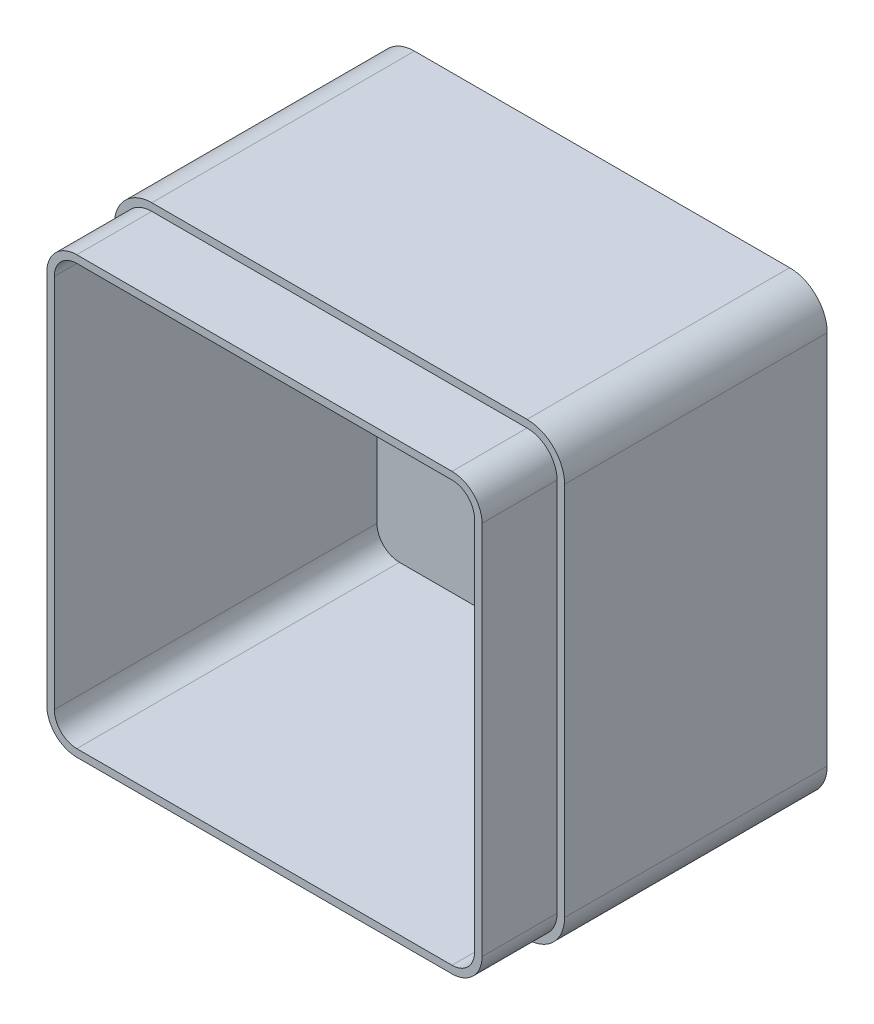
SolidWorks part; units mm, degrees
ref_plane "Front Plane" through (0, 0, 0) normal (0, 0, 1) x (1, 0, 0)
ref_plane "Top Plane" through (0, 0, 0) normal (0, 1, 0) x (1, 0, 0)
ref_plane "Right Plane" through (0, 0, 0) normal (1, 0, 0) x (0, 0, -1)
sketch "Sketch2" plane through (0, 0, 0) normal (0, 0, 1) x (1, 0, 0)
  line L1 (-46.1775, 31.2287) -> (73.8225, 31.2287)
  line L2 (-46.1775, 31.2287) -> (-46.1775, -88.7713)
  line L3 (-46.1775, -88.7713) -> (73.8225, -88.7713)
  line L4 (73.8225, 31.2287) -> (73.8225, -88.7713)
  dimension "D1" = 120
  dimension "D2" = 120
extrude "Boss-Extrude1" add sketch "Sketch2" along normal blind 90
fillet "Fillet1" radius 10 4 edges at (-46.1775, -88.7713, 45) (73.8225, -88.7713, 45) (-46.1775, 31.2287, 45) (73.8225, 31.2287, 45)
shell "Shell1" thickness 4
sketch "Sketch3" plane through (0, 0, 90) normal (0, 0, 1) x (1, 0, 0)
  line L0 (-44.1775, 21.2287) -> (-44.1775, -78.7713)
  line L1 (-36.1775, -86.7713) -> (63.8225, -86.7713)
  line L2 (71.8225, -78.7713) -> (71.8225, 21.2287)
  line L3 (63.8225, 29.2287) -> (-36.1775, 29.2287)
  line L4 (-46.1775, 21.2287) -> (-46.1775, -78.7713)
  line L5 (-36.1775, -88.7713) -> (63.8225, -88.7713)
  line L6 (73.8225, -78.7713) -> (73.8225, 21.2287)
  line L7 (63.8225, 31.2287) -> (-36.1775, 31.2287)
  line L8 (-46.1775, 21.2287) -> (-46.1775, -78.7713)
  line L9 (-36.1775, -88.7713) -> (63.8225, -88.7713)
  line L10 (73.8225, -78.7713) -> (73.8225, 21.2287)
  line L11 (63.8225, 31.2287) -> (-36.1775, 31.2287)
  arc A0 (-44.1775, -78.7713) -> (-36.1775, -86.7713) centre (-36.1775, -78.7713) ccw
  arc A1 (63.8225, -86.7713) -> (71.8225, -78.7713) centre (63.8225, -78.7713) ccw
  arc A2 (71.8225, 21.2287) -> (63.8225, 29.2287) centre (63.8225, 21.2287) ccw
  arc A3 (-36.1775, 29.2287) -> (-44.1775, 21.2287) centre (-36.1775, 21.2287) ccw
  arc A4 (-46.1775, -78.7713) -> (-36.1775, -88.7713) centre (-36.1775, -78.7713) ccw
  arc A5 (63.8225, -88.7713) -> (73.8225, -78.7713) centre (63.8225, -78.7713) ccw
  arc A6 (73.8225, 21.2287) -> (63.8225, 31.2287) centre (63.8225, 21.2287) ccw
  arc A7 (-36.1775, 31.2287) -> (-46.1775, 21.2287) centre (-36.1775, 21.2287) ccw
  arc A8 (-46.1775, -78.7713) -> (-36.1775, -88.7713) centre (-36.1775, -78.7713) ccw
  arc A9 (63.8225, -88.7713) -> (73.8225, -78.7713) centre (63.8225, -78.7713) ccw
  arc A10 (73.8225, 21.2287) -> (63.8225, 31.2287) centre (63.8225, 21.2287) ccw
  arc A11 (-36.1775, 31.2287) -> (-46.1775, 21.2287) centre (-36.1775, 21.2287) ccw
  dimension "D1" = 0
  dimension "D2" = 2
extrude "Cut-Extrude1" cut sketch "Sketch3" against normal blind 20
